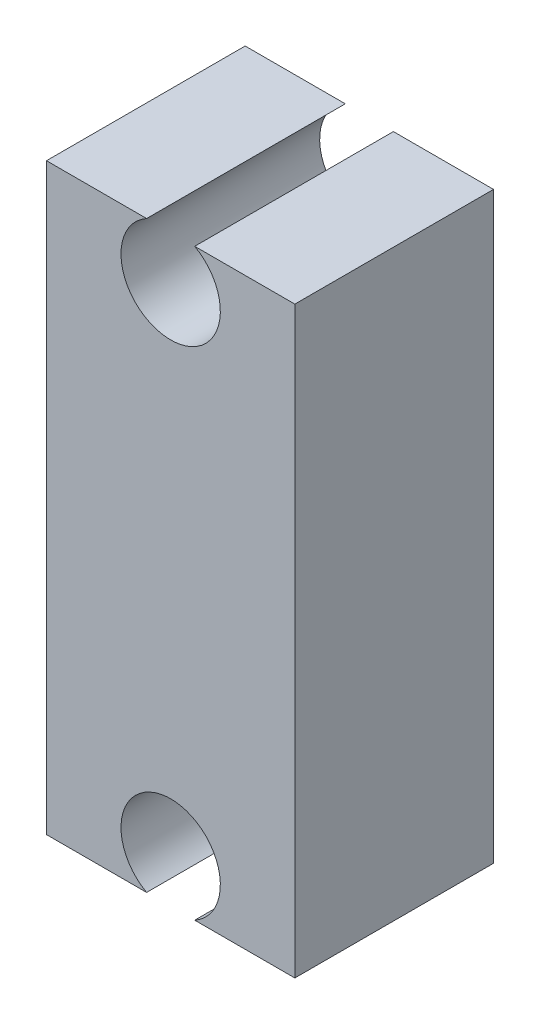
SolidWorks part; units mm, degrees
ref_plane "Front Plane" through (0, 0, 0) normal (0, 0, 1) x (1, 0, 0)
ref_plane "Top Plane" through (0, 0, 0) normal (0, 1, 0) x (1, 0, 0)
ref_plane "Right Plane" through (0, 0, 0) normal (1, 0, 0) x (0, 0, -1)
sketch "Sketch1" plane through (0, 0, 0) normal (0, 0, 1) x (1, 0, 0)
  line L1 (-12.7, 13.9935) -> (0, 13.9935)
  line L2 (-12.7, 13.9935) -> (-12.7, -15.8515)
  line L3 (-12.7, -15.8515) -> (0, -15.8515)
  line L4 (0, 13.9935) -> (0, -15.8515)
  dimension "D1" = 12.7
  dimension "D2" = 29.845
extrude "Boss-Extrude1" add sketch "Sketch1" along normal blind 10.16
sketch "Sketch2" plane through (0, 0, 10.16) normal (0, 0, 1) x (1, 0, 0)
  line L0 (-12.7, -15.8515) -> (0, -15.8515) construction
  circle A0 centre (-6.35, 11.771) radius 2.54
  circle A1 centre (-6.35, -13.629) radius 2.54
  point P4 (0, 0)
  dimension "D1" = 5.08
  dimension "D2" = 25.4
  dimension "D3" = 2.2225
extrude "Cut-Extrude1" cut sketch "Sketch2" against normal blind 10.16
